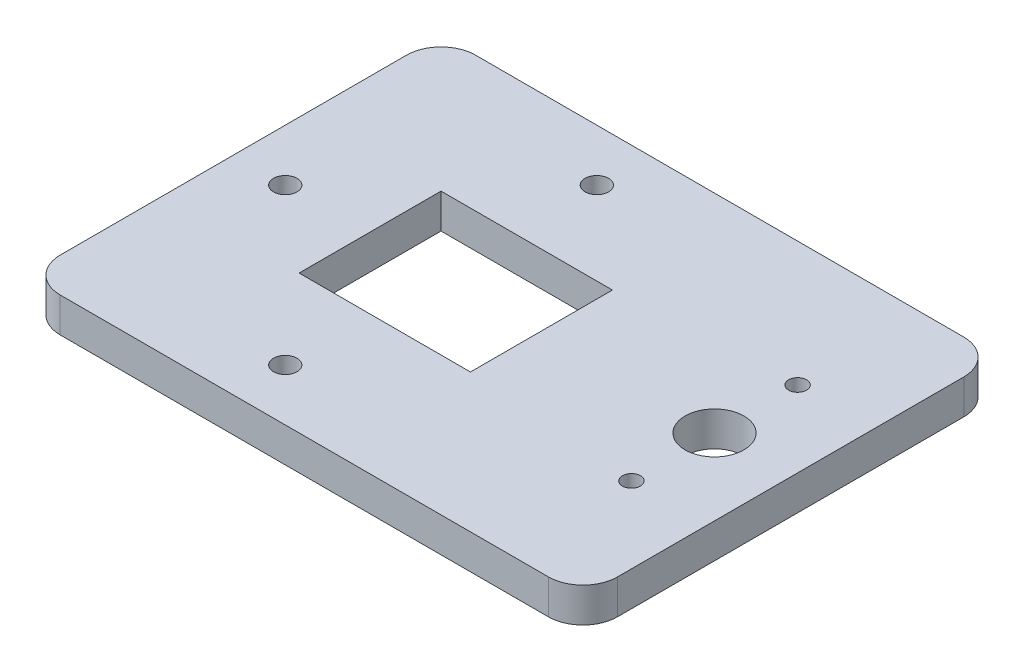
SolidWorks part; units mm, degrees
ref_plane "前视基准面" through (0, 0, 0) normal (0, 0, 1) x (1, 0, 0)
ref_plane "上视基准面" through (0, 0, 0) normal (0, 1, 0) x (1, 0, 0)
ref_plane "右视基准面" through (0, 0, 0) normal (1, 0, 0) x (0, 0, -1)
other "Configuration Table"
sketch "草图1" plane through (0, 0, 0) normal (0, 1, 0) x (1, 0, 0)
  line L1 (-100.5, -60) -> (60.5, -60)
  line L2 (-100.5, -60) -> (-100.5, 60)
  line L3 (-100.5, 60) -> (60.5, 60)
  line L4 (60.5, -60) -> (60.5, 60)
  line L5 (-100.5, -60) -> (60.5, 60) construction
  line L6 (-100.5, 60) -> (60.5, -60) construction
  dimension "D1" = 161
  dimension "D2" = 120
extrude "凸台-拉伸1" add sketch "草图1" along normal blind 10
fillet "圆角1" radius 10 2 edges at (60.5, 5, -60) (60.5, 5, 60)
sketch "草图2" plane through (0, 10, 0) normal (0, 1, 0) x (1, 0, 0)
  line L9 (-12, -20) -> (-61.5, -20)
  line L10 (-12, -20) -> (-12, 21)
  line L11 (-12, 21) -> (-61.5, 21)
  line L12 (-61.5, -20) -> (-61.5, 21)
  line L13 (-12, -20) -> (-61.5, 21) construction
  line L14 (-12, 21) -> (-61.5, -20) construction
  line L18 (-100.5, -60) -> (50.5, -60) construction
  dimension "D1" = 49.5
  dimension "D2" = 41
  dimension "D3" = 40
extrude "切除-拉伸1" cut sketch "草图2" against normal blind 10
sketch "草图3" plane through (0, 10, 0) normal (0, 1, 0) x (1, 0, 0)
  circle A0 centre (38.5, 0) radius 8.5
  dimension "D1" = 17
extrude "切除-拉伸2" cut sketch "草图3" against normal blind 10
fillet "圆角2" radius 10 2 edges at (-100.5, 5, -60) (-100.5, 5, 60)
sketch "草图5" plane through (0, 0, 0) normal (0, -1, 0) x (1, 0, 0)
  line L0 (-90.5, 60) -> (50.5, 60) construction
  line L1 (-100.5, -50) -> (-100.5, 50) construction
  line L2 (50.5, -60) -> (-90.5, -60) construction
  circle A0 centre (-40.5, 45) radius 3.4
  circle A1 centre (-85.5, 0) radius 3.4
  circle A2 centre (-40.5, -45) radius 3.4
  dimension "D1" = 6.8
  dimension "D2" = 6.8
  dimension "D3" = 6.8
  dimension "D4" = 15
  dimension "D5" = 15
  dimension "D6" = 15
extrude "切除-拉伸4" cut sketch "草图5" against normal through all
cosmetic thread "装饰螺纹线1" parameters "D1"=10, "D2"=7.8
cosmetic thread "装饰螺纹线2" parameters "D1"=10, "D2"=7.8
cosmetic thread "装饰螺纹线3" parameters "D1"=10, "D2"=7.8
sketch "草图6" plane through (0, 10, 0) normal (0, 1, 0) x (1, 0, 0)
  line L0 (38.5, 0) -> (38.5, 60) construction
  line L1 (50.5, 60) -> (-90.5, 60) construction
  line L2 (38.5, 0) -> (38.5, -60) construction
  line L3 (-90.5, -60) -> (50.5, -60) construction
  circle A0 centre (38.5, 24) radius 2.6
  circle A1 centre (38.5, -24) radius 2.6
  circle A2 centre (38.5, 0) radius 8.5 construction
  dimension "D1" = 5.2
  dimension "D2" = 5.2
  dimension "D3" = 24
  dimension "D4" = 24
extrude "切除-拉伸5" cut sketch "草图6" against normal blind 10
cosmetic thread "装饰螺纹线4" parameters "D1"=10, "D2"=6.2
cosmetic thread "装饰螺纹线5" parameters "D1"=10, "D2"=6.2
